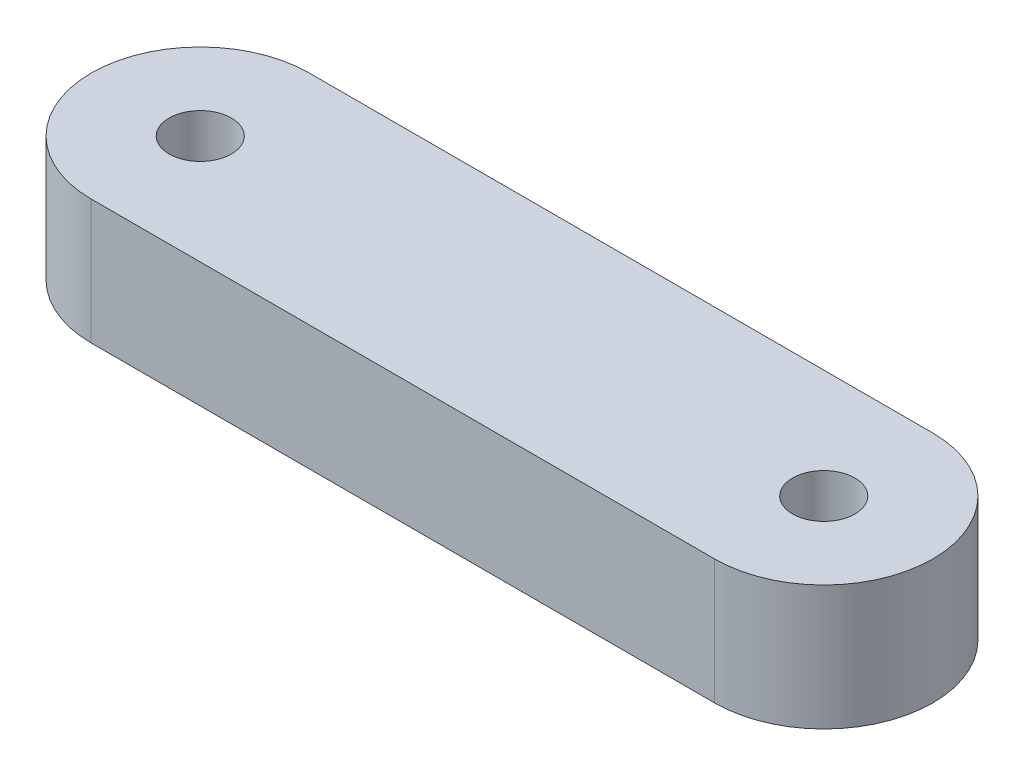
SolidWorks part; units mm, degrees
ref_plane "Front Plane" through (0, 0, 0) normal (0, 0, 1) x (1, 0, 0)
ref_plane "Top Plane" through (0, 0, 0) normal (0, 1, 0) x (1, 0, 0)
ref_plane "Right Plane" through (0, 0, 0) normal (1, 0, 0) x (0, 0, -1)
sketch "Sketch1" plane through (0, 0, 0) normal (0, 1, 0) x (1, 0, 0)
  line L0 (0, -8.7467) -> (-50, -8.7467)
  line L1 (0, 8.7467) -> (-50, 8.7467)
  circle A0 centre (0, 0) radius 2.5
  arc A1 (0, 8.7467) -> (0, -8.7467) centre (0, 0) cw
  circle A2 centre (-50, 0) radius 2.5
  arc A3 (-50, 8.7467) -> (-50, -8.7467) centre (-50, 0) ccw
  dimension "D1" = 5
  dimension "D2" = 50
extrude "Boss-Extrude1" add sketch "Sketch1" along normal blind 10
